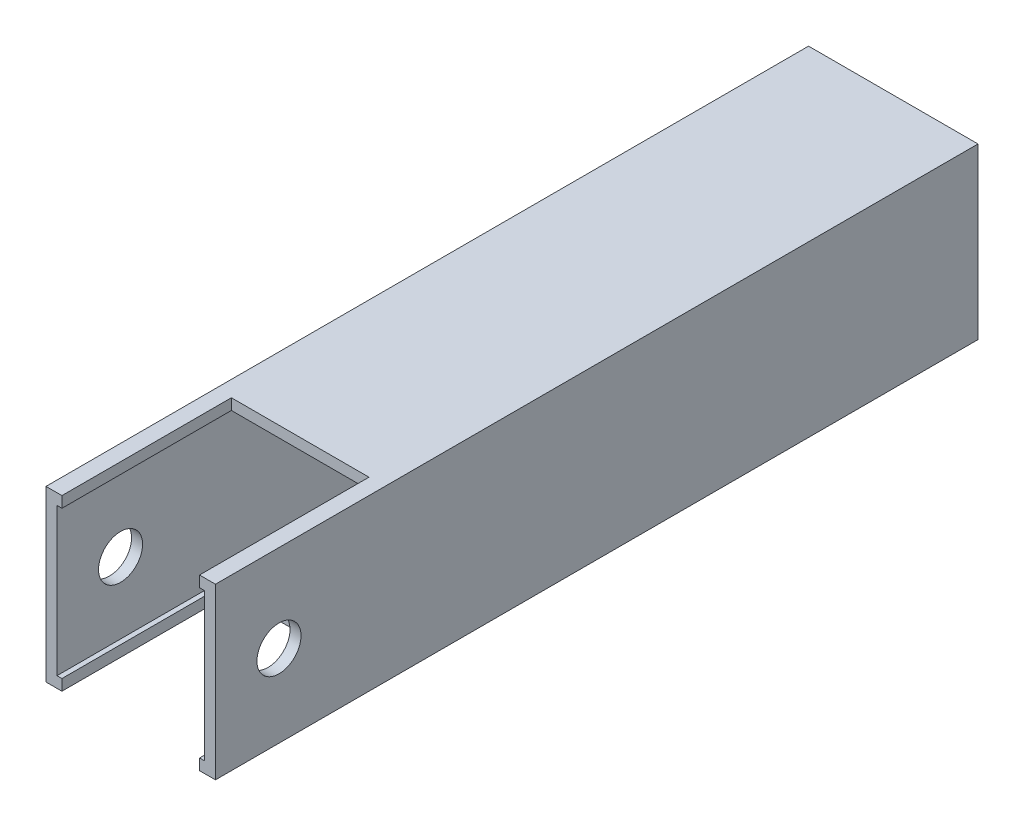
SolidWorks part; units mm, degrees
ref_plane "Front Plane" through (0, 0, 0) normal (0, 0, 1) x (1, 0, 0)
ref_plane "Top Plane" through (0, 0, 0) normal (0, 1, 0) x (1, 0, 0)
ref_plane "Right Plane" through (0, 0, 0) normal (1, 0, 0) x (0, 0, -1)
sketch "Sketch1" plane through (0, 0, 0) normal (0, 0, 1) x (1, 0, 0)
  line L1 (-51.2814, -31.3505) -> (-25.8814, -31.3505)
  line L2 (-51.2814, -31.3505) -> (-51.2814, -5.9505)
  line L3 (-51.2814, -5.9505) -> (-25.8814, -5.9505)
  line L4 (-25.8814, -31.3505) -> (-25.8814, -5.9505)
  dimension "D1" = 25.4
  dimension "D2" = 25.4
extrude "Boss-Extrude1" add sketch "Sketch1" along normal blind 114.3
sketch "Sketch3" plane through (0, 0, 114.3) normal (0, 0, 1) x (1, 0, 0)
  line L0 (-51.2814, -5.9505) -> (-51.2814, -31.3505) construction
  line L1 (-49.6304, -7.6015) -> (-27.5324, -7.6015)
  line L2 (-49.6304, -7.6015) -> (-49.6304, -29.6995)
  line L3 (-49.6304, -29.6995) -> (-27.5324, -29.6995)
  line L4 (-27.5324, -7.6015) -> (-27.5324, -29.6995)
  line L5 (-49.6304, -7.6015) -> (-27.5324, -29.6995) construction
  line L6 (-49.6304, -29.6995) -> (-27.5324, -7.6015) construction
  line L7 (-25.8814, -5.9505) -> (-51.2814, -5.9505) construction
  line L8 (-25.8814, -31.3505) -> (-25.8814, -5.9505) construction
  line L9 (-51.2814, -31.3505) -> (-25.8814, -31.3505) construction
  point P0 (-38.5814, -18.6505)
  dimension "D1" = 1.651
  dimension "D2" = 1.651
  dimension "D3" = 1.651
  dimension "D4" = 1.651
extrude "Cut-Extrude1" cut sketch "Sketch3" against normal through all
sketch "Sketch4" plane through (0, -5.9505, 0) normal (0, 1, 0) x (1, 0, 0)
  line L0 (-25.8814, -114.3) -> (-51.2814, -114.3) construction
  line L1 (-48.8938, -139.7) -> (-28.269, -139.7)
  line L2 (-48.8938, -139.7) -> (-48.8938, -88.9)
  line L3 (-48.8938, -88.9) -> (-28.269, -88.9)
  line L4 (-28.269, -139.7) -> (-28.269, -88.9)
  line L5 (-48.8938, -139.7) -> (-28.269, -88.9) construction
  line L6 (-48.8938, -88.9) -> (-28.269, -139.7) construction
  line L7 (-51.2814, -114.3) -> (-51.2814, 0) construction
  line L8 (-25.8814, -114.3) -> (-25.8814, 0) construction
  line L9 (-25.8814, 0) -> (-51.2814, 0) construction
  point P0 (-38.5814, -114.3)
  dimension "D1" = 2.3876
  dimension "D2" = 2.3876
  dimension "D3" = 88.9
extrude "Cut-Extrude2" cut sketch "Sketch4" against normal through all contours L2 L1 L4 L3
sketch "Sketch5" plane through (-51.2814, 0, 0) normal (-1, 0, 0) x (0, 0, 1)
  line L1 (114.3, -31.3505) -> (0, -31.3505) construction
  circle A0 centre (104.775, -19.0446) radius 3.302
  dimension "D2" = 6.604
  dimension "D3" = 12.3059
extrude "Cut-Extrude3" cut sketch "Sketch5" against normal through all
